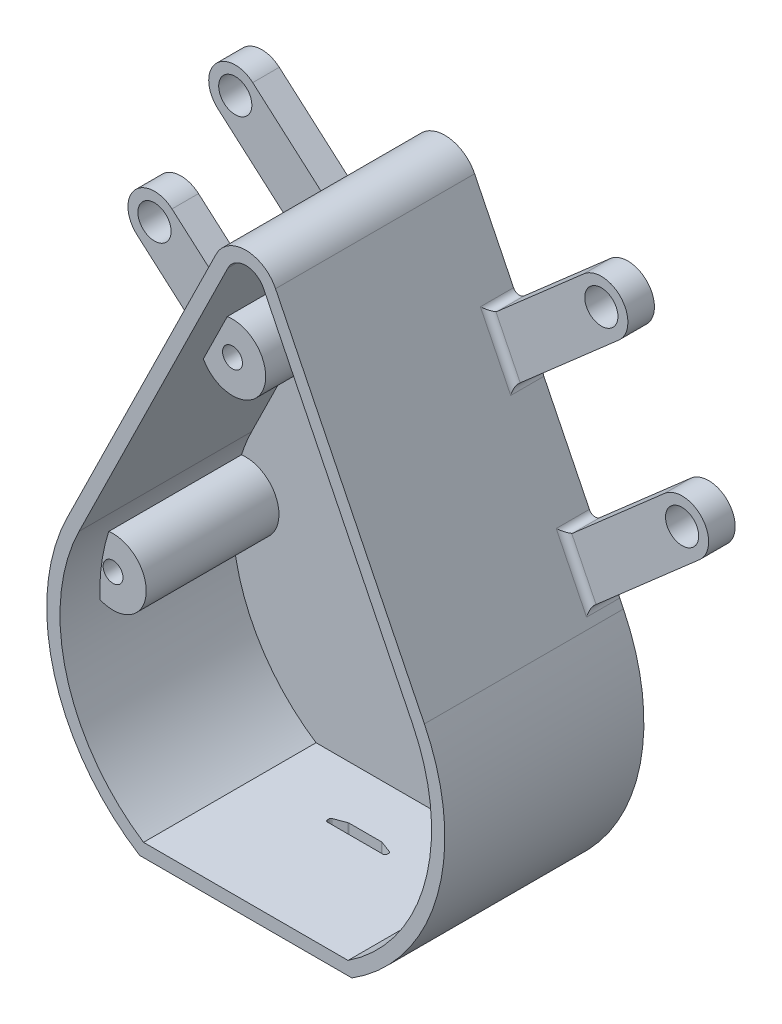
SolidWorks part; units mm, degrees
ref_plane "Plan de face" through (0, 0, 0) normal (0, 0, 1) x (1, 0, 0)
ref_plane "Plan de dessus" through (0, 0, 0) normal (0, 1, 0) x (1, 0, 0)
ref_plane "Plan de droite" through (0, 0, 0) normal (1, 0, 0) x (0, 0, -1)
sketch "Esquisse2" plane through (0, 0, 0) normal (0, 0, 1) x (1, 0, 0)
  line L0 (-26.9176, 13.2455) -> (-4.4863, 58.8304)
  line L1 (4.4863, 58.8304) -> (26.9176, 13.2455)
  line L2 (-16, -25.3772) -> (16, -25.3772)
  arc A0 (-26.9176, 13.2455) -> (-16, -25.3772) centre (0, 0) ccw
  arc A1 (16, -25.3772) -> (26.9176, 13.2455) centre (0, 0) ccw
  arc A2 (-4.4863, 58.8304) -> (4.4863, 58.8304) centre (0, 56.6228) cw
  point P13 (0, 67.9474)
  dimension "D1" = 5
  dimension "D2" = 30
  dimension "D5" = 32
  dimension "D6" = 82
extrude "Base shell" add sketch "Esquisse2" along normal blind 30
shell "Coque1" thickness 2
sketch "Esquisse4" plane through (0, 0, 0) normal (0, 0, 1) x (1, 0, 0)
  line L0 (-15.4113, -23.3772) -> (15.4113, -23.3772) construction
  line L5 (-15.4113, -23.3772) -> (15.4113, -23.3772) construction
  line L6 (-2.6918, 57.9474) -> (-25.1231, 12.3625) construction
  line L7 (-8.7871, 45.5605) -> (-12.3924, 38.2339)
  line L8 (0, 95.2434) -> (0, -67.9994) construction
  line L9 (8.7871, 45.5605) -> (12.3924, 38.2339)
  arc A0 (-12.3924, 38.2339) -> (-8.7871, 45.5605) centre (-8, 40.6228) ccw
  arc A1 (-27.9833, -0.967) -> (-26.653, 8.58) centre (-26, 3.6228) ccw
  circle A2 centre (-8, 40.6228) radius 1.5
  circle A3 centre (-26, 3.6228) radius 1.5
  arc A5 (-25.1231, 12.3625) -> (-15.4113, -23.3772) centre (0, 0) ccw construction
  arc A6 (27.9833, -0.967) -> (26.653, 8.58) centre (26, 3.6228) cw
  circle A7 centre (26, 3.6228) radius 1.5
  circle A8 centre (8, 40.6228) radius 1.5
  arc A9 (12.3924, 38.2339) -> (8.7871, 45.5605) centre (8, 40.6228) cw
  arc A10 (-25.1231, 12.3625) -> (-15.4113, -23.3772) centre (0, 0) ccw construction
  arc A11 (-26.653, 8.58) -> (-27.9833, -0.967) centre (0, 0) ccw
  arc A12 (15.4113, -23.3772) -> (25.1231, 12.3625) centre (0, 0) ccw construction
  arc A13 (27.9833, -0.967) -> (26.653, 8.58) centre (0, 0) ccw
  dimension "D1" = 10
  dimension "D2" = 10
  dimension "D5" = 3
  dimension "D6" = 3
  dimension "D7" = 27
  dimension "D8" = 64
  dimension "D9" = 26
  dimension "D10" = 8
extrude "Boss.-Extru.2" add sketch "Esquisse4" along normal blind 24
sketch "Esquisse6" plane through (0, 0, 0) normal (0, 0, 1) x (1, 0, 0)
  line L0 (0, -35.5326) -> (0, 64.2233) construction
  line L1 (0, 36.1657) -> (-24.9514, 58.0096)
  line L2 (-30.221, 51.9904) -> (0, 25.5332)
  line L3 (0, 25.5332) -> (0, 36.1657)
  line L4 (-4.4863, 58.8304) -> (-26.9176, 13.2455) construction
  line L5 (0, 2.939) -> (-37.1222, 35.4379)
  line L6 (-42.3918, 29.4187) -> (0, -7.6936)
  line L8 (0, 2.939) -> (0, -7.6936)
  line L9 (-12.1708, -58.1043) -> (-12.1708, 41.6516) construction
  line L10 (-12.1708, 2.9614) -> (-12.1708, 13.594) [skipped]
  arc A0 (-24.9514, 58.0096) -> (-30.221, 51.9904) centre (-27.5862, 55) ccw
  circle A1 centre (-27.5862, 55) radius 2.5
  arc A2 (-37.1222, 35.4379) -> (-42.3918, 29.4187) centre (-39.757, 32.4283) ccw
  circle A3 centre (-39.757, 32.4283) radius 2.5
  dimension "D1" = 4
  dimension "D2" = 5
  dimension "D3" = 75
  dimension "D7" = 17
  dimension "D4" = 18
  dimension "D5" = 55
  dimension "D6" = 2
extrude "Boss.-Extru.3" add sketch "Esquisse6" along normal up to surface (4 mm away) up to face at (0, 19.0461, 4)
mirror "Symétrie1" about plane through (0, 0, 0) normal (1, 0, 0) of "Boss.-Extru.3"
fillet "Congé2" radius 1 12 edges at (22.3577, 22.5122, 2) (24.186, 18.7966, 4) (14.5871, 38.3035, 2) (10.9303, 45.7348, 2) (12.7587, 42.0192, 4) (-22.3577, 22.5122, 2) (-24.186, 18.7966, 4) (-10.9303, 45.7348, 2) (-14.5871, 38.3035, 2) (-12.7587, 42.0192, 4) (-26.0144, 15.0809, 2) (26.0144, 15.0809, 2)
sketch "Esquisse8" plane through (0, -25.3772, 0) normal (0, -1, 0) x (1, 0, 0)
  line L9 (-16, 0) -> (16, 0) construction
  line L10 (0, -2.1987) -> (0, 14.786) construction
  line L15 (2.5, 12) -> (-2.5, 12)
  line L16 (-2.5, 12) -> (-4.5, 12.75)
  line L17 (-4.5, 12.75) -> (-4.5, 13.5)
  line L18 (-4.5, 13.5) -> (4.5, 13.5)
  line L19 (4.5, 12.75) -> (4.5, 13.5)
  line L20 (2.5, 12) -> (4.5, 12.75)
  point P11 (0, 13.5)
  point P12 (0, 12)
  dimension "D1" = 2.5
  dimension "D2" = 4.5
  dimension "D3" = 1.5
  dimension "D4" = 0.75
  dimension "D5" = 12
extrude "Enlèv. mat.-Extru.1" cut sketch "Esquisse8" against normal up to surface (2 mm away) up to face at (0, -23.3772, 17)
fillet "Congé3" radius 0.3 6 edges at (4.5, -24.3772, 13.5) (-4.5, -24.3772, 13.5) (4.5, -24.3772, 12.75) (2.5, -24.3772, 12) (-2.5, -24.3772, 12) (-4.5, -24.3772, 12.75)
